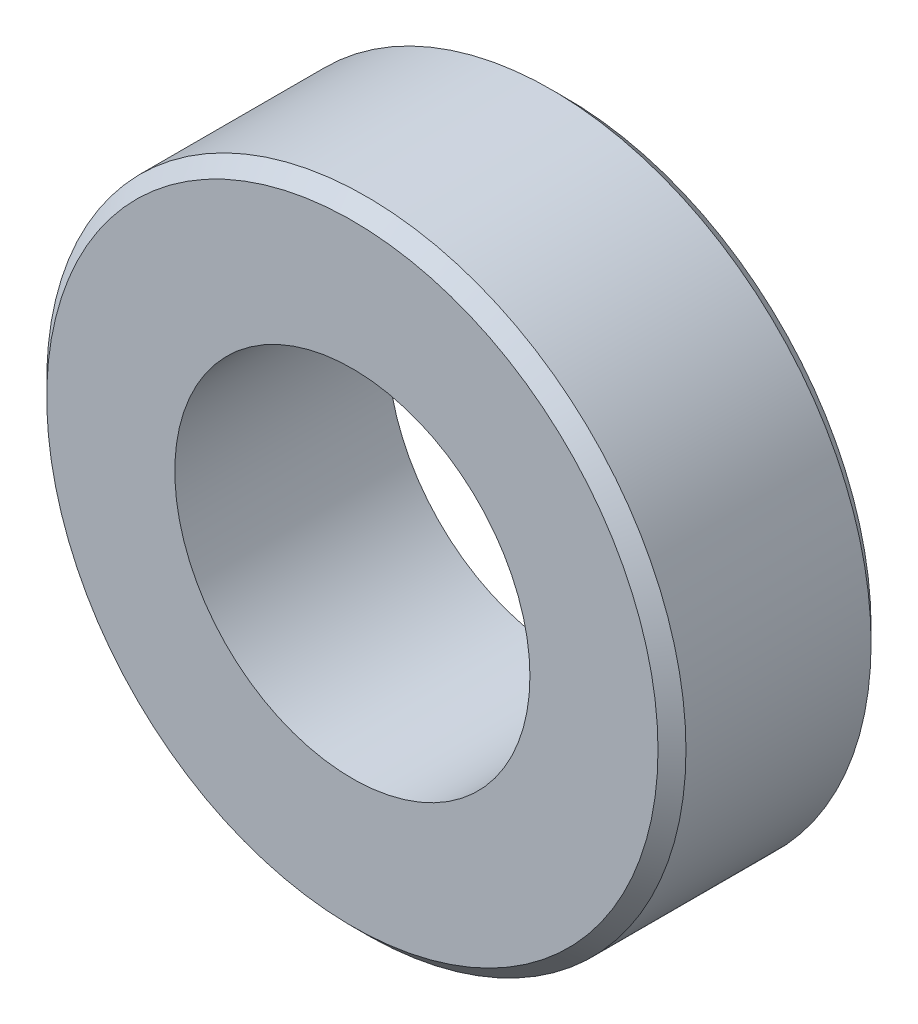
SolidWorks part; units mm, degrees
ref_plane "Front Plane" through (0, 0, 0) normal (0, 0, 1) x (1, 0, 0)
ref_plane "Top Plane" through (0, 0, 0) normal (0, 1, 0) x (1, 0, 0)
ref_plane "Right Plane" through (0, 0, 0) normal (1, 0, 0) x (0, 0, -1)
sketch "Sketch1" plane through (0, 0, 0) normal (0, 0, 1) x (1, 0, 0)
  circle A0 centre (0, 0) radius 6.35
  circle A1 centre (0, 0) radius 11.43
  dimension "D1" = 22.86
  dimension "D2" = 12.7
extrude "Boss-Extrude1" add sketch "Sketch1" along normal blind 7.62
chamfer "Chamfer1" distance 0.5 angle 45 2 edges at (11.43, 0, 0) (11.43, 0, 7.62)
